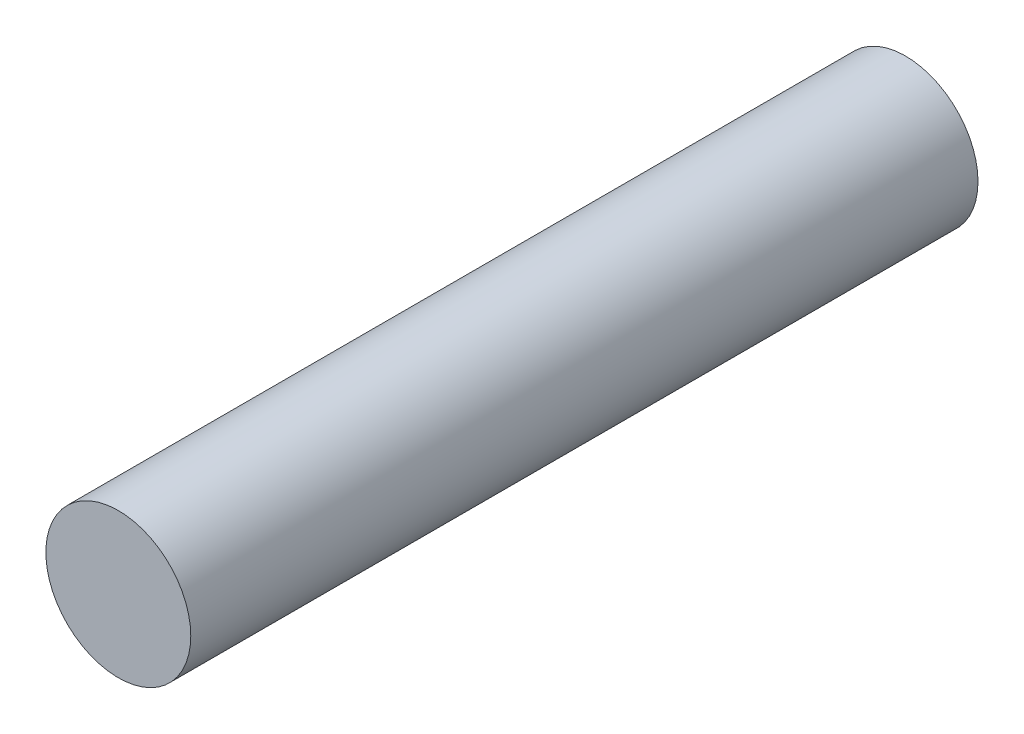
SolidWorks part; units mm, degrees
ref_plane "Plan de face" through (0, 0, 0) normal (0, 0, 1) x (1, 0, 0)
ref_plane "Plan de dessus" through (0, 0, 0) normal (0, 1, 0) x (1, 0, 0)
ref_plane "Plan de droite" through (0, 0, 0) normal (1, 0, 0) x (0, 0, -1)
sketch "Esquisse1" plane through (0, 0, 0) normal (0, 0, 1) x (1, 0, 0)
  circle A0 centre (0, 0) radius 10.125
  dimension "D1" = 20.25
extrude "Boss.-Extru.1" add sketch "Esquisse1" along normal blind 110
